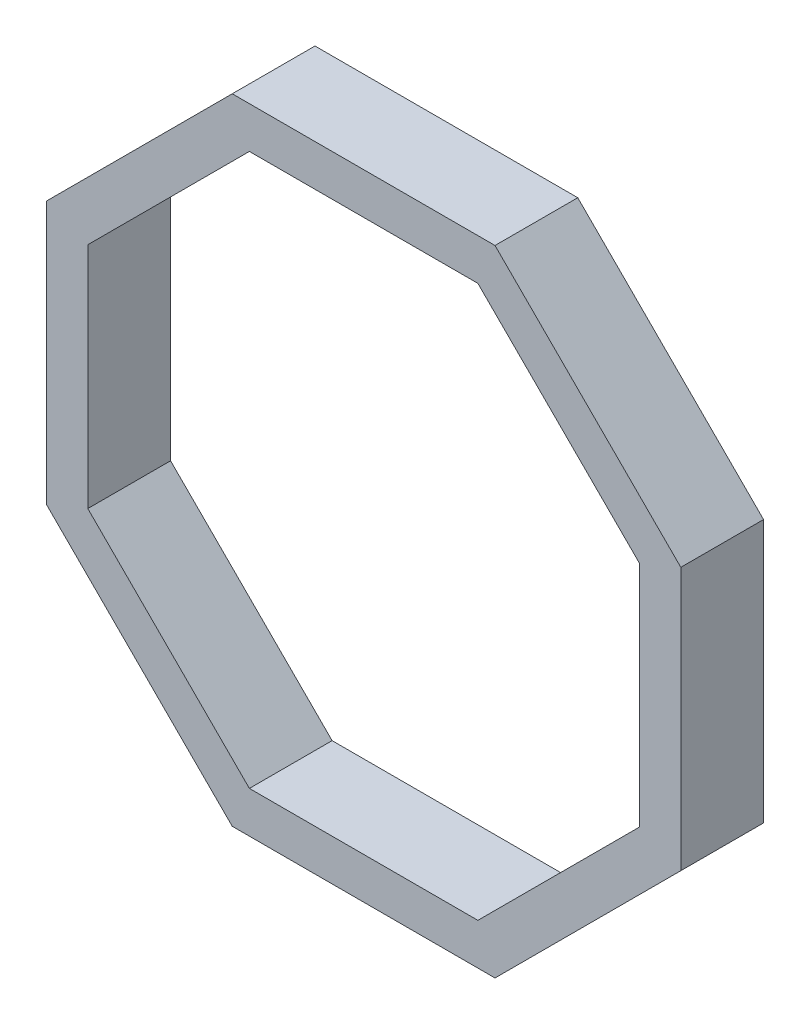
SolidWorks part; units mm, degrees
ref_plane "Plano frontal" through (0, 0, 0) normal (0, 0, 1) x (1, 0, 0)
ref_plane "Plano superior" through (0, 0, 0) normal (0, 1, 0) x (1, 0, 0)
ref_plane "Plano direito" through (0, 0, 0) normal (1, 0, 0) x (0, 0, -1)
sketch "Esboço1" plane through (0, 0, 0) normal (0, 0, 1) x (1, 0, 0)
  line L1 (115, 47.6346) -> (47.6346, 115)
  line L2 (47.6346, 115) -> (-47.6346, 115)
  line L3 (-47.6346, 115) -> (-115, 47.6346)
  line L4 (-115, 47.6346) -> (-115, -47.6346)
  line L5 (-115, -47.6346) -> (-47.6346, -115)
  line L6 (-47.6346, -115) -> (47.6346, -115)
  line L7 (47.6346, -115) -> (115, -47.6346)
  line L8 (115, -47.6346) -> (115, 47.6346)
  line L9 (100, 41.4214) -> (41.4214, 100)
  line L10 (41.4214, 100) -> (-41.4214, 100)
  line L11 (-41.4214, 100) -> (-100, 41.4214)
  line L12 (-100, 41.4214) -> (-100, -41.4214)
  line L13 (-100, -41.4214) -> (-41.4214, -100)
  line L14 (-41.4214, -100) -> (41.4214, -100)
  line L15 (41.4214, -100) -> (100, -41.4214)
  line L16 (100, -41.4214) -> (100, 41.4214)
  circle A0 centre (0, 0) radius 115 construction
  circle A1 centre (0, 0) radius 100 construction
extrude "Ressalto-extrusão1" add sketch "Esboço1" along normal blind 30
